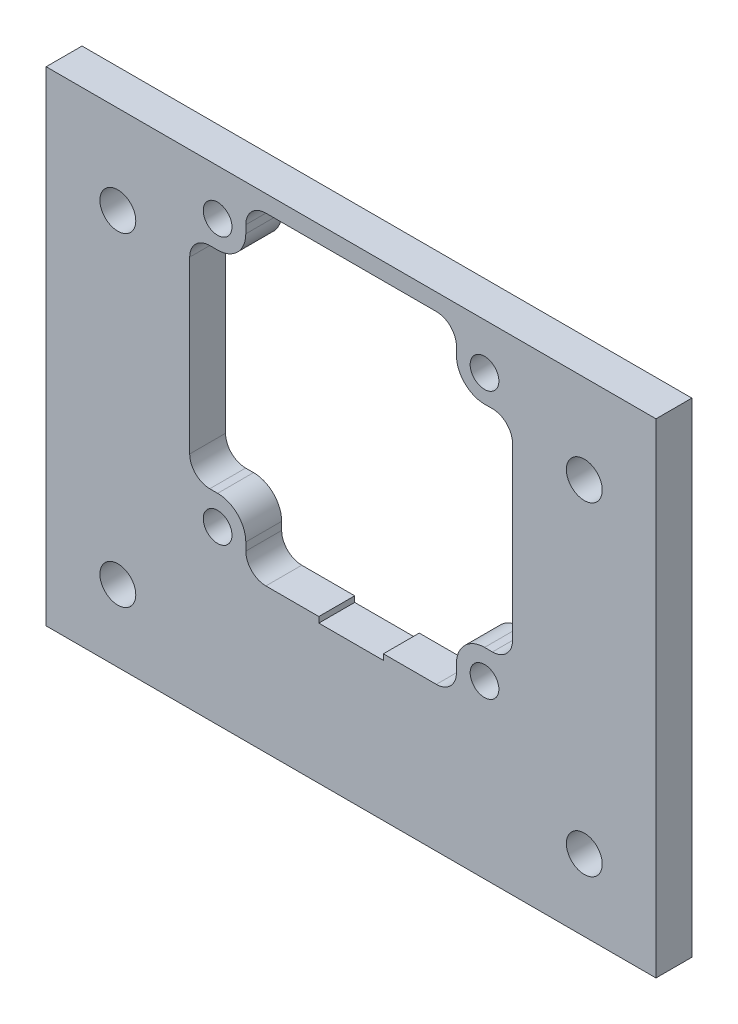
SolidWorks part; units mm, degrees
ref_plane "Front Plane" through (0, 0, 0) normal (0, 0, 1) x (1, 0, 0)
ref_plane "Top Plane" through (0, 0, 0) normal (0, 1, 0) x (1, 0, 0)
ref_plane "Right Plane" through (0, 0, 0) normal (1, 0, 0) x (0, 0, -1)
sketch "Sketch1" plane through (0, 0, 0) normal (0, 0, 1) x (1, 0, 0)
  line L0 (-2.667, -1.7227) -> (-2.667, 1.7227) construction
  line L1 (28.575, -28.575) -> (-28.575, -28.575) construction
  line L2 (28.575, -28.575) -> (28.575, 28.575) construction
  line L3 (28.575, 28.575) -> (-28.575, 28.575) construction
  line L4 (-28.575, -28.575) -> (-28.575, 28.575) construction
  line L5 (28.575, -28.575) -> (-28.575, 28.575) construction
  line L6 (28.575, 28.575) -> (-28.575, -28.575) construction
  line L7 (23.622, -23.622) -> (-23.622, -23.622) construction
  line L8 (23.622, -23.622) -> (23.622, 23.622) construction
  line L9 (23.622, 23.622) -> (-23.622, 23.622) construction
  line L10 (-23.622, -23.622) -> (-23.622, 23.622) construction
  line L11 (23.622, -23.622) -> (-23.622, 23.622) construction
  line L12 (23.622, 23.622) -> (-23.622, -23.622) construction
  line L14 (53.975, 31.75) -> (-53.975, 31.75)
  line L15 (53.975, 31.75) -> (53.975, 0)
  line L16 (53.975, 0) -> (-53.975, 0)
  line L17 (-53.975, 31.75) -> (-53.975, 0)
  line L18 (0, 0) -> (0, 31.75) construction
  line L19 (53.975, 15.875) -> (-53.975, 15.875) construction
  line L20 (53.975, -53.975) -> (-53.975, -53.975)
  line L21 (53.975, -53.975) -> (53.975, 0)
  line L22 (53.975, 0) -> (-53.975, 0)
  line L23 (-53.975, -53.975) -> (-53.975, 0)
  line L24 (0, 0) -> (0, -53.975) construction
  line L25 (53.975, -26.9875) -> (-53.975, -26.9875) construction
  circle A0 centre (-23.622, 23.622) radius 2.54 construction
  circle A1 centre (23.622, 23.622) radius 2.54 construction
  circle A2 centre (-23.622, -23.622) radius 2.54 construction
  circle A3 centre (23.622, -23.622) radius 2.54 construction
  point P0 (0, 0)
  point P6 (0, 0)
  point P15 (0, 0)
  point P16 (0, 15.875)
  point P18 (0, 3.175)
  point P19 (0, 28.575)
  point P20 (0, 19.05)
  point P21 (-23.622, -26.162)
  point P26 (0, 0)
  point P27 (0, -26.9875)
  dimension "D3" = 5.08
  dimension "D4" = 107.95
  dimension "D5" = 53.975
  dimension "D1" = 107.95
  dimension "Width" = 57.15
  dimension "D2" = 31.75
  dimension "CenterToCenter" = 47.244
sketch "Sketch3" plane through (0, 0, 0) normal (0, 0, 1) x (1, 0, 0)
  line L1 (-28.575, -28.575) -> (-28.575, 28.575) construction
  line L2 (28.575, 28.575) -> (-28.575, 28.575) construction
  line L3 (28.575, -28.575) -> (28.575, 28.575) construction
  line L4 (28.575, -28.575) -> (-28.575, -28.575) construction
  line L5 (-28.575, -25.4) -> (-28.575, 25.4)
  line L6 (25.4, 28.575) -> (-25.4, 28.575)
  line L7 (28.575, -25.4) -> (28.575, 25.4)
  line L8 (25.4, -28.575) -> (-25.4, -28.575)
  arc A4 (-28.575, 25.4) -> (-25.4, 28.575) centre (-25.4, 25.4) cw
  arc A5 (25.4, 28.575) -> (28.575, 25.4) centre (25.4, 25.4) cw
  arc A6 (28.575, -25.4) -> (25.4, -28.575) centre (25.4, -25.4) cw
  arc A7 (-25.4, -28.575) -> (-28.575, -25.4) centre (-25.4, -25.4) cw
  dimension "D1" = 3.175
extrude "Boss-Extrude1" add sketch "Sketch1" along normal blind 6.35 contours L14 L17 L16 L15 | L23 L20 L21 L16
sketch "Sketch11" plane through (0, 0, 0) normal (0, 0, -1) x (-1, 0, 0)
  line L4 (-23.622, 23.622) -> (-23.622, -23.622)
  line L5 (-23.622, -23.622) -> (23.622, -23.622)
  line L6 (-23.622, 23.622) -> (23.622, 23.622)
  line L7 (23.622, 23.622) -> (23.622, -23.622)
  circle A0 centre (23.622, -23.622) radius 2.54
  circle A1 centre (-23.622, -23.622) radius 2.54
  circle A2 centre (-23.622, 23.622) radius 2.54
  circle A3 centre (23.622, 23.622) radius 2.54
  dimension "D1" = 47.244
  dimension "D2" = 47.244
extrude "Cut-Extrude2" cut sketch "Sketch11" against normal blind 7.62 contours A2 | A3 | A0 | A1
sketch "Sketch12" plane through (0, 0, 0) normal (0, 0, -1) x (-1, 0, 0)
  line L0 (-0.0085, 28.7524) -> (-0.0085, 0.1774) construction
  line L1 (-0.0085, 0.1774) -> (-28.5835, 0.1774) construction
  line L2 (-25.0275, 18.821) -> (-23.6305, 18.821)
  line L3 (-18.6521, 23.7994) -> (-18.6521, 25.1964)
  line L4 (-28.5835, 15.265) -> (-28.5835, -14.9102)
  line L5 (15.0791, 28.7524) -> (-15.0961, 28.7524)
  line L6 (28.5665, -14.9102) -> (28.5665, 15.265)
  line L7 (18.6351, 23.7994) -> (18.6351, 25.1964)
  line L8 (25.0105, 18.821) -> (23.6135, 18.821)
  line L9 (25.0105, -18.4662) -> (23.6135, -18.4662)
  line L10 (18.6351, -23.4446) -> (18.6351, -24.8416)
  line L11 (15.0791, -28.3976) -> (-15.0961, -28.3976)
  line L12 (-18.6521, -23.4446) -> (-18.6521, -24.8416)
  line L13 (-25.0275, -18.4662) -> (-23.6305, -18.4662)
  line L15 (-5.7235, -29.4136) -> (5.7065, -29.4136)
  line L16 (-5.7235, -29.4136) -> (-5.7235, -28.3976)
  line L17 (-5.7235, -28.3976) -> (5.7065, -28.3976)
  line L18 (5.7065, -29.4136) -> (5.7065, -28.3976)
  arc A0 (-25.0275, 18.821) -> (-28.5835, 15.265) centre (-25.0275, 15.265) ccw
  arc A1 (-15.0961, 28.7524) -> (-18.6521, 25.1964) centre (-15.0961, 25.1964) ccw
  arc A2 (-23.6305, 18.821) -> (-18.6521, 23.7994) centre (-23.6305, 23.7994) ccw
  arc A3 (23.6135, 18.821) -> (18.6351, 23.7994) centre (23.6135, 23.7994) cw
  arc A4 (15.0791, 28.7524) -> (18.6351, 25.1964) centre (15.0791, 25.1964) cw
  arc A5 (25.0105, 18.821) -> (28.5665, 15.265) centre (25.0105, 15.265) cw
  arc A6 (25.0105, -18.4662) -> (28.5665, -14.9102) centre (25.0105, -14.9102) ccw
  arc A7 (15.0791, -28.3976) -> (18.6351, -24.8416) centre (15.0791, -24.8416) ccw
  arc A8 (23.6135, -18.4662) -> (18.6351, -23.4446) centre (23.6135, -23.4446) ccw
  arc A9 (-23.6305, -18.4662) -> (-18.6521, -23.4446) centre (-23.6305, -23.4446) cw
  arc A10 (-15.0961, -28.3976) -> (-18.6521, -24.8416) centre (-15.0961, -24.8416) cw
  arc A11 (-25.0275, -18.4662) -> (-28.5835, -14.9102) centre (-25.0275, -14.9102) cw
  point P43 (-0.0085, -28.3976)
  point P44 (-0.0085, -28.3976)
  point P45 (-93.3192, -4.9991)
  dimension "D3" = 1.016
  dimension "D4" = 11.43
extrude "Cut-Extrude3" cut sketch "Sketch12" against normal blind 7.62 contours A11 L13 A9 L12 A10 L11 A7 L10 A8 L9 A6 L6 A5 L8 A3 L7 A4 L5 A1 L3 A2 L2 A0 L4 | L15 L18 L11 L16
sketch "Sketch13" plane through (0, 0, 0) normal (0, 0, -1) x (-1, 0, 0)
  line L0 (-41.2835, 31.75) -> (-41.2835, -53.975) construction
  line L1 (-53.975, 31.75) -> (53.975, 31.75) construction
  line L2 (-53.975, -53.975) -> (53.975, -53.975) construction
  line L3 (-28.5835, 15.265) -> (-28.5835, -14.9102) construction
  line L4 (15.0791, 28.7524) -> (-15.0961, 28.7524) construction
  line L5 (0, 31.75) -> (0, -53.975) construction
  circle A0 centre (-41.2835, 16.0524) radius 3.175
  circle A1 centre (-41.2835, -41.275) radius 3.175
  circle A2 centre (41.2835, -41.275) radius 3.175
  circle A3 centre (41.2835, 16.0524) radius 3.175
  dimension "D1" = 6.35
  dimension "D2" = 12.7
  dimension "D3" = 12.7
  dimension "D4" = 12.7
extrude "Cut-Extrude4" cut sketch "Sketch13" against normal blind 7.62 contours A0 | A1 | A2 | A3
